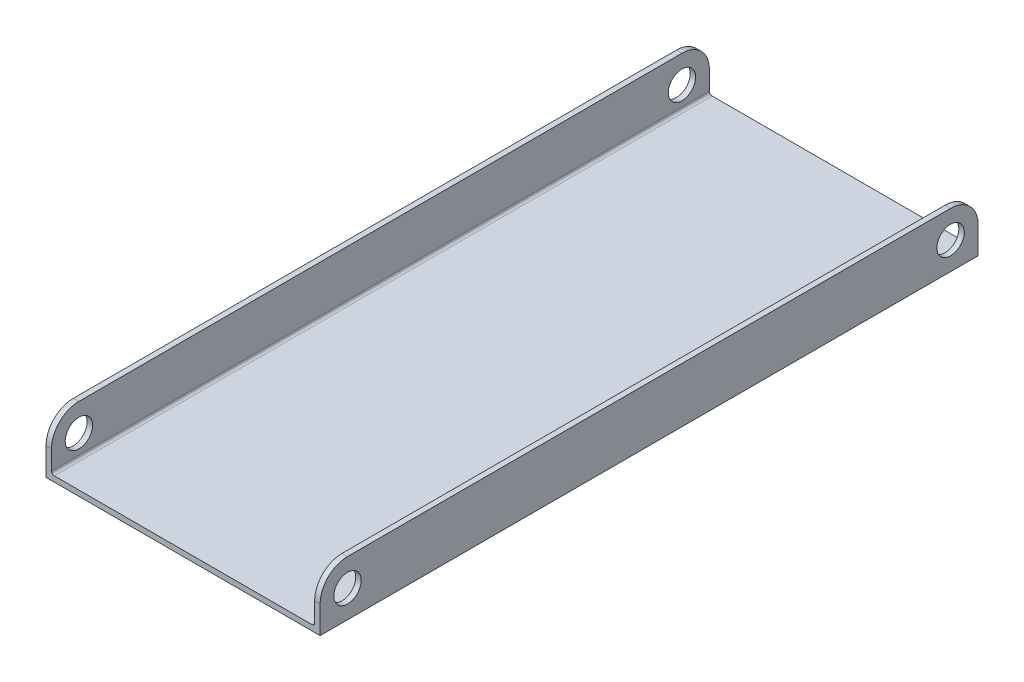
SolidWorks part; units mm, degrees
material "AISI 1020"
ref_plane "Front Plane" through (0, 0, 0) normal (0, 0, 1) x (1, 0, 0)
ref_plane "Top Plane" through (0, 0, 0) normal (0, 1, 0) x (1, 0, 0)
ref_plane "Right Plane" through (0, 0, 0) normal (1, 0, 0) x (0, 0, -1)
sketch "Sketch1" plane through (0, 0, 0) normal (0, 0, 1) x (1, 0, 0)
  line L0 (0, 0) -> (-63.5, 0)
  line L1 (-63.5, 0) -> (-63.5, 12.7)
  line L2 (-63.5, 12.7) -> (-62.23, 12.7)
  line L3 (-62.23, 12.7) -> (-62.23, 1.27)
  line L4 (-62.23, 1.27) -> (-1.27, 1.27)
  line L5 (-1.27, 1.27) -> (-1.27, 12.7)
  line L6 (-1.27, 12.7) -> (0, 12.7)
  line L7 (0, 12.7) -> (0, 0)
  line L8 (-31.75, 0) -> (-31.75, 32.031) construction
  dimension "D1" = 63.5
  dimension "D2" = 60.96
  dimension "D3" = 1.27
  dimension "D4" = 12.7
extrude "Boss-Extrude1" add sketch "Sketch1" against normal blind 152.4
fillet "Fillet1" radius 0.635 2 edges at (-1.27, 1.27, -76.2) (-62.23, 1.27, -76.2)
fillet "Fillet2" radius 6.35 4 edges at (-62.865, 12.7, -152.4) (-0.635, 12.7, -152.4) (-0.635, 12.7, 0) (-62.865, 12.7, 0)
sketch "Sketch3" plane through (0, 0, 0) normal (1, 0, 0) x (0, 0, -1)
  circle A0 centre (6.35, 6.35) radius 3.175
  circle A1 centre (146.05, 6.35) radius 3.175
  dimension "D1" = 6.35
extrude "Cut-Extrude1" cut sketch "Sketch3" against normal blind 152.4
